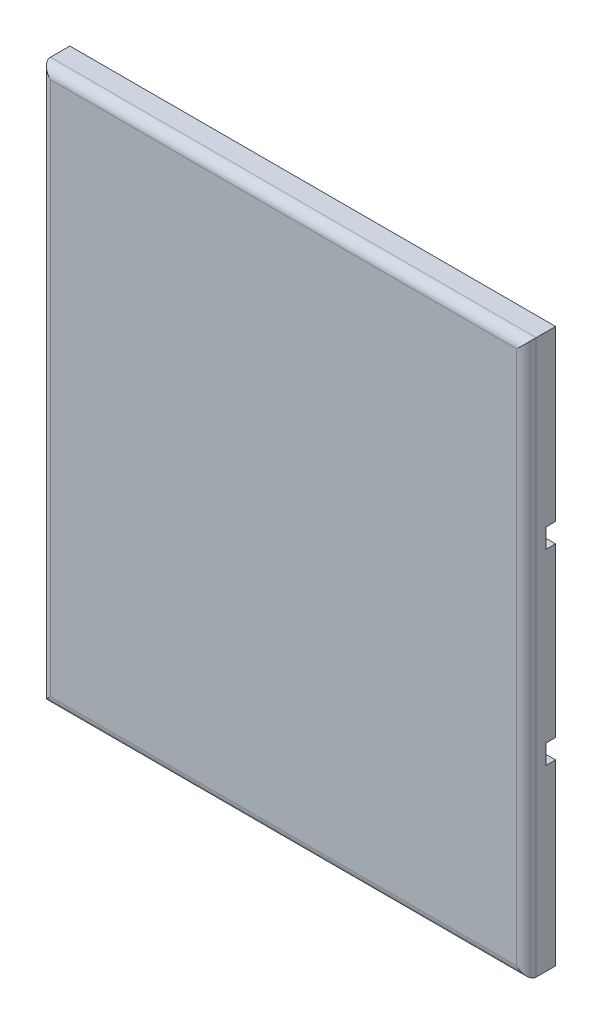
SolidWorks part; units mm, degrees
ref_plane "Front Plane" through (0, 0, 0) normal (0, 0, 1) x (1, 0, 0)
ref_plane "Top Plane" through (0, 0, 0) normal (0, 1, 0) x (1, 0, 0)
ref_plane "Right Plane" through (0, 0, 0) normal (1, 0, 0) x (0, 0, -1)
sketch "Sketch1" plane through (0, 0, 0) normal (0, 0, 1) x (1, 0, 0)
  line L1 (0, 0) -> (-500, 0)
  line L2 (0, 0) -> (0, -570)
  line L3 (0, -570) -> (-500, -570)
  line L4 (-500, 0) -> (-500, -570)
  dimension "D1" = 570
  dimension "D2" = 500
extrude "Boss-Extrude1" add sketch "Sketch1" along normal blind 30
fillet "Fillet1" radius 10 4 edges at (-500, -285, 30) (-250, -570, 30) (0, -285, 30) (-250, 0, 30)
ref_plane "Plane1" through (0, -570, 0) normal (1, 0, 0) x (0, 0, -1)
sketch "Sketch3" plane through (0, 0, 0) normal (0, 0, 1) x (1, 0, 0)
  line L0 (24.1246, -386.4105) -> (24.1246, -366.4105)
  line L1 (-500, -570) -> (0, -570)
  line L2 (-500, -570) -> (-500, 0)
  line L3 (-500, 0) -> (0, 0)
  line L4 (0, -570) -> (0, 0)
  line L9 (-524.1246, -386.4105) -> (24.1246, -386.4105)
  line L10 (-524.1246, -386.4105) -> (-524.1246, -366.4105)
  line L11 (-524.1246, -366.4105) -> (24.1246, -366.4105)
  line L15 (40.8853, -193.8214) -> (-575.0867, -193.8214)
  line L16 (40.8853, -193.8214) -> (40.8853, -173.8214)
  line L17 (40.8853, -173.8214) -> (-575.0867, -173.8214)
  line L18 (-575.0867, -193.8214) -> (-575.0867, -173.8214)
  dimension "D2" = 20
extrude "Cut-Extrude1" cut sketch "Sketch3" along normal blind 10 contours L11 L2 L9 L4 | L11 L10 L9 L2 | L11 L4 L9 L0 | L16 L17 L4 L15 | L4 L17 L2 L15 | L18 L15 L2 L17
